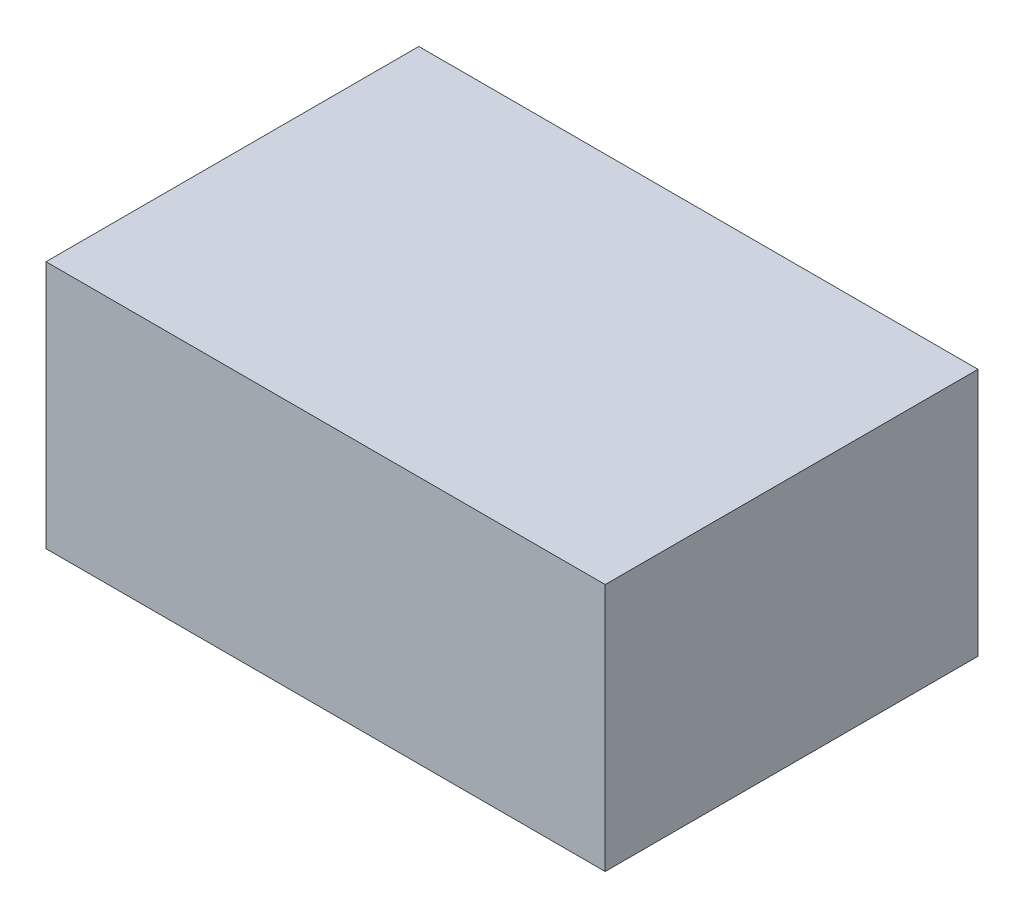
SolidWorks part; units mm, degrees
ref_plane "Front Plane" through (0, 0, 0) normal (0, 0, 1) x (1, 0, 0)
ref_plane "Top Plane" through (0, 0, 0) normal (0, 1, 0) x (1, 0, 0)
ref_plane "Right Plane" through (0, 0, 0) normal (1, 0, 0) x (0, 0, -1)
sketch "Sketch2" plane through (0, 0, 0) normal (0, 1, 0) x (1, 0, 0)
  line L0 (-22.1391, 33.777) -> (63.5859, 33.777)
  line L1 (63.5859, 33.777) -> (63.5859, -23.373)
  line L2 (63.5859, -23.373) -> (-22.1391, -23.373)
  line L3 (-22.1391, -23.373) -> (-22.1391, 33.777)
  dimension "D1" = 85.725
  dimension "D2" = 57.15
extrude "Boss-Extrude1" add sketch "Sketch2" along normal blind 38.1
